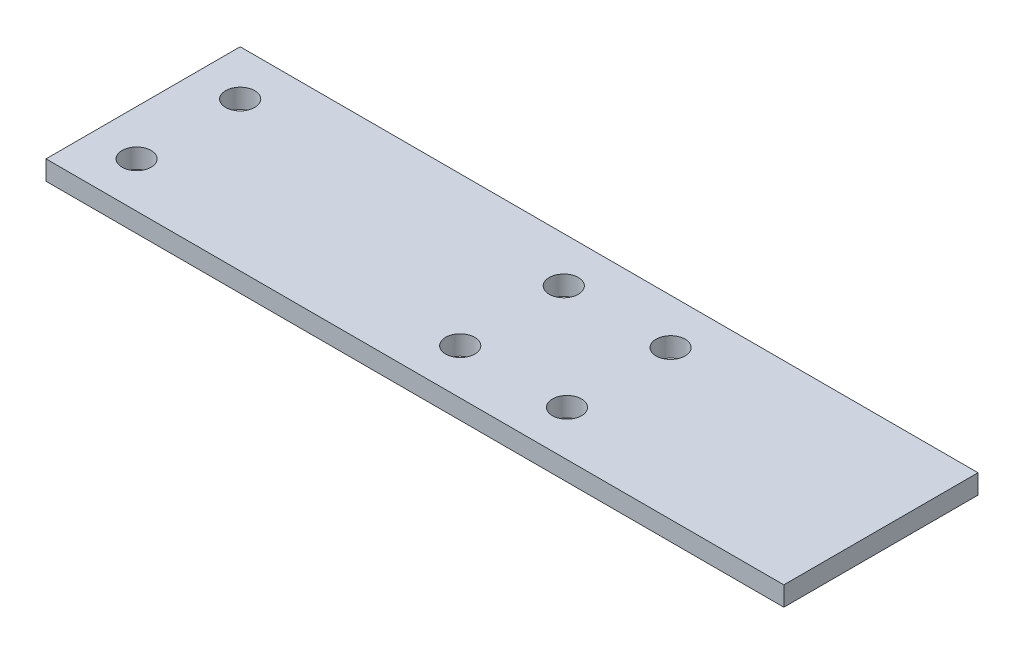
SolidWorks part; units mm, degrees
ref_plane "Front Plane" through (0, 0, 0) normal (0, 0, 1) x (1, 0, 0)
ref_plane "Top Plane" through (0, 0, 0) normal (0, 1, 0) x (1, 0, 0)
ref_plane "Right Plane" through (0, 0, 0) normal (1, 0, 0) x (0, 0, -1)
sketch "Sketch1" plane through (0, 0, 0) normal (0, 1, 0) x (1, 0, 0)
  line L0 (0, 16) -> (0, 0) construction
  line L1 (0, 0) -> (50, 0) construction
  line L2 (0, 16) -> (50, 16) construction
  line L3 (-7, 23) -> (-7, -7)
  line L4 (-7, 23) -> (57, 23)
  line L5 (50, 16) -> (56.5, 16) construction
  line L6 (57, -7) -> (-7, -7)
  line L7 (57, 23) -> (107, 23)
  line L8 (107, 23) -> (107, -7)
  line L9 (107, -7) -> (57, -7)
  line L10 (56.5, 16) -> (66.5, 16) construction
  circle A0 centre (0, 0) radius 2.25
  circle A1 centre (0, 16) radius 2.25
  circle A2 centre (50, 0) radius 2.25
  circle A3 centre (50, 16) radius 2.25
  circle A4 centre (66.5, 16) radius 2.25
  circle A5 centre (66.5, 0) radius 2.25
  point P11 (-7, 8)
  point P12 (0, 8)
  dimension "D1" = 4.5
  dimension "D2" = 16
  dimension "D3" = 50
  dimension "D4" = 30
  dimension "D5" = 7
  dimension "D6" = 6.5
  dimension "D7" = 50
  dimension "D8" = 10
extrude "Boss-Extrude1" add sketch "Sketch1" along normal blind 3
